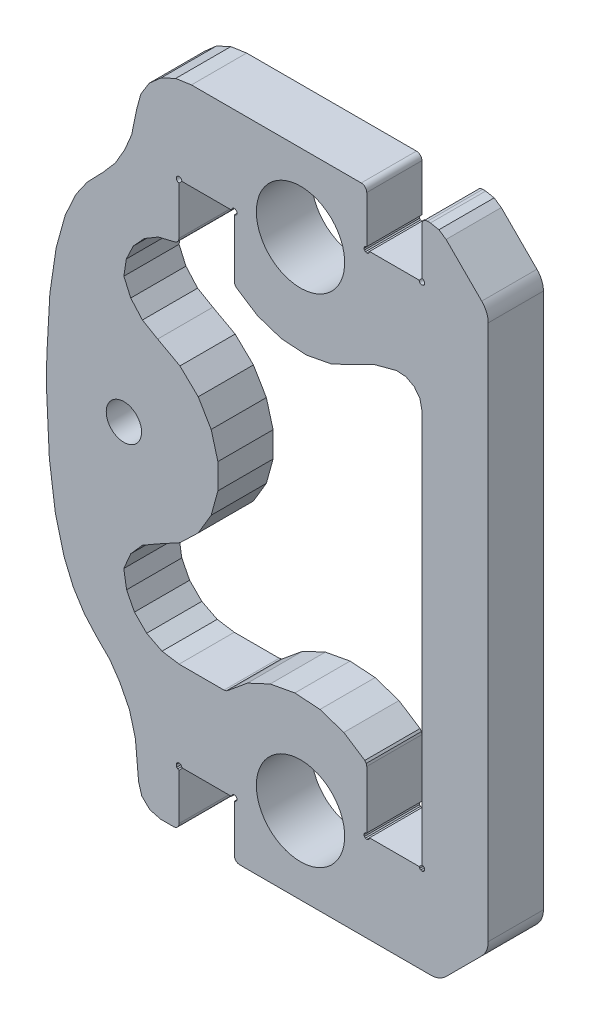
SolidWorks part; units mm, degrees
ref_plane "Plan de face" through (0, 0, 0) normal (0, 0, 1) x (1, 0, 0)
ref_plane "Plan de dessus" through (0, 0, 0) normal (0, 1, 0) x (1, 0, 0)
ref_plane "Plan de droite" through (0, 0, 0) normal (1, 0, 0) x (0, 0, -1)
ref_plane "Plan1" through (0, 0, 0) normal (0, 0, -1) x (-1, 0, 0)
sketch "Esquisse1" plane through (0, 0, 0) normal (0, 0, -1) x (-1, 0, 0)
  line L0 (-17, 50.75) -> (-17, 51.125) construction
  line L1 (-16.75, 51) -> (-17.0786, 51) construction
  line L2 (-12, 50.75) -> (-12, 51.4552) construction
  line L3 (-12.4344, 51) -> (-11.6303, 51) construction
  line L4 (-34, 54.25) -> (-34, 53.1966) construction
  line L5 (-33.75, 54) -> (-34.1708, 54) construction
  line L16 (-8.0397, 5.194) -> (-7.5117, 7.1637)
  line L17 (-7.5117, 7.1637) -> (-6.6375, 8.8943)
  line L18 (-6.6375, 8.8943) -> (-5.7344, 10.2147)
  line L19 (-5.7344, 10.2147) -> (-4.5295, 11.4233)
  line L20 (-4.5295, 11.4233) -> (-3.4265, 12.6596)
  line L21 (-3.4265, 12.6596) -> (-2.4227, 14.24)
  line L22 (-2.4227, 14.24) -> (-1.5781, 16.2347)
  line L23 (-1.5781, 16.2347) -> (-0.788, 19.2781)
  line L24 (-0.788, 19.2781) -> (-0.2469, 23.2647)
  line L25 (-0.2469, 23.2647) -> (-0.0081, 28.2691)
  line L26 (-0.0081, 28.2691) -> (0, 29.5)
  line L27 (0, 29.5) -> (-0.0151, 31.1645)
  line L28 (-0.0151, 31.1645) -> (-0.2937, 36.2357)
  line L29 (-0.2937, 36.2357) -> (-0.8642, 40.1026)
  line L30 (-0.8642, 40.1026) -> (-1.6815, 43.0589)
  line L31 (-1.6815, 43.0589) -> (-2.6679, 45.2058)
  line L32 (-2.6679, 45.2058) -> (-3.6838, 46.6619)
  line L33 (-3.6838, 46.6619) -> (-5.1213, 48.1528)
  line L34 (-5.1213, 48.1528) -> (-6.2218, 49.4228)
  line L35 (-6.2218, 49.4228) -> (-7.0842, 50.913)
  line L36 (-7.0842, 50.913) -> (-7.7057, 52.3865)
  line L37 (-7.7057, 52.3865) -> (-8.155, 54.6026)
  line L38 (-8.155, 54.6026) -> (-8.5346, 55.9968)
  line L39 (-8.5346, 55.9968) -> (-9.297, 57.2242)
  line L40 (-9.297, 57.2242) -> (-10.3785, 58.1823)
  line L41 (-10.3785, 58.1823) -> (-11.6888, 58.7912)
  line L42 (-11.6888, 58.7912) -> (-13.1186, 59)
  line L43 (-13.1186, 59) -> (-28.5, 59)
  line L47 (-29, 58.5) -> (-29, 54.25)
  line L48 (-29, 54.25) -> (-28.875, 54.2165)
  line L49 (-28.875, 54.2165) -> (-28.7835, 54.125)
  line L50 (-28.7835, 54.125) -> (-28.75, 54)
  line L51 (-28.75, 54) -> (-28.7835, 53.875)
  line L52 (-28.7835, 53.875) -> (-28.875, 53.7835)
  line L53 (-28.875, 53.7835) -> (-29, 53.75)
  line L54 (-29, 53.75) -> (-29.125, 53.7835)
  line L55 (-29.125, 53.7835) -> (-29.2165, 53.875)
  line L56 (-29.2165, 53.875) -> (-29.25, 54)
  line L57 (-29.25, 54) -> (-33.75, 54)
  line L67 (-34, 54.25) -> (-34, 58.5)
  line L71 (-34.5, 59) -> (-34.7716, 59)
  line L72 (-34.7716, 59) -> (-35.5369, 58.8478)
  line L73 (-35.5369, 58.8478) -> (-36.1858, 58.4142)
  line L74 (-36.1858, 58.4142) -> (-39.4142, 55.1858)
  line L77 (-40, 53.7716) -> (-40, 5.2284)
  line L80 (-39.4142, 3.8142) -> (-36.1858, 0.5858)
  line L83 (-34.7716, 0) -> (-17.5, 0)
  line L87 (-17, 0.5) -> (-17, 4.75)
  line L88 (-17, 4.75) -> (-17.125, 4.7835)
  line L89 (-17.125, 4.7835) -> (-17.2165, 4.875)
  line L90 (-17.2165, 4.875) -> (-17.25, 5)
  line L91 (-17.25, 5) -> (-17.2165, 5.125)
  line L92 (-17.2165, 5.125) -> (-17.125, 5.2165)
  line L93 (-17.125, 5.2165) -> (-17, 5.25)
  line L94 (-17, 5.25) -> (-16.875, 5.2165)
  line L95 (-16.875, 5.2165) -> (-16.7835, 5.125)
  line L96 (-16.7835, 5.125) -> (-16.75, 5)
  line L97 (-16.75, 5) -> (-12.25, 5)
  line L98 (-12.25, 5) -> (-12.2165, 5.125)
  line L99 (-12.2165, 5.125) -> (-12.125, 5.2165)
  line L100 (-12.125, 5.2165) -> (-12, 5.25)
  line L101 (-12, 5.25) -> (-11.875, 5.2165)
  line L102 (-11.875, 5.2165) -> (-11.7835, 5.125)
  line L103 (-11.7835, 5.125) -> (-11.75, 5)
  line L104 (-11.75, 5) -> (-11.7835, 4.8104)
  line L105 (-11.7835, 4.8104) -> (-11.875, 4.7189)
  line L106 (-11.875, 4.7189) -> (-12, 4.6854)
  line L107 (-12, 4.6854) -> (-12, 0.5)
  line L111 (-11.5, 0) -> (-10.332, 0)
  line L112 (-10.332, 0) -> (-9.3522, 0.2564)
  line L113 (-9.3522, 0.2564) -> (-8.6237, 0.96)
  line L114 (-8.6237, 0.96) -> (-8.3332, 1.9302)
  line L115 (-8.3332, 1.9302) -> (-8.0397, 5.194)
  line L128 (-27.8538, 44.4211) -> (-25.788, 43.4427)
  line L129 (-25.788, 43.4427) -> (-23.5422, 43.0164)
  line L130 (-23.5422, 43.0164) -> (-21.2615, 43.1695)
  line L131 (-21.2615, 43.1695) -> (-19.093, 43.8923)
  line L132 (-19.093, 43.8923) -> (-17.1765, 45.138)
  line L133 (-17.1765, 45.138) -> (-17.0463, 45.3092)
  line L134 (-17.0463, 45.3092) -> (-17, 45.5193)
  line L135 (-17, 45.5193) -> (-17, 50.75)
  line L145 (-16.75, 51) -> (-12.25, 51)
  line L155 (-12, 50.75) -> (-12, 46.4126)
  line L156 (-12, 46.4126) -> (-11.9404, 46.1759)
  line L157 (-11.9404, 46.1759) -> (-11.7758, 45.9956)
  line L158 (-11.7758, 45.9956) -> (-11.5455, 45.9147)
  line L159 (-11.5455, 45.9147) -> (-10.113, 45.5656)
  line L160 (-10.113, 45.5656) -> (-8.8446, 44.814)
  line L161 (-8.8446, 44.814) -> (-7.8506, 43.7251)
  line L162 (-7.8506, 43.7251) -> (-7.2174, 42.3937)
  line L163 (-7.2174, 42.3937) -> (-7, 40.9354)
  line L164 (-7, 40.9354) -> (-7.6191, 39.5311)
  line L165 (-7.6191, 39.5311) -> (-8.678, 38.3351)
  line L166 (-8.678, 38.3351) -> (-10.0601, 37.534)
  line L167 (-10.0601, 37.534) -> (-12.0779, 36.4347)
  line L168 (-12.0779, 36.4347) -> (-13.7325, 34.8404)
  line L169 (-13.7325, 34.8404) -> (-14.906, 32.8648)
  line L170 (-14.906, 32.8648) -> (-15.5144, 30.649)
  line L171 (-15.5144, 30.649) -> (-15.5144, 28.3512)
  line L172 (-15.5144, 28.3512) -> (-14.906, 26.1354)
  line L173 (-14.906, 26.1354) -> (-13.7325, 24.1598)
  line L174 (-13.7325, 24.1598) -> (-12.0779, 22.5655)
  line L175 (-12.0779, 22.5655) -> (-10.0601, 21.4662)
  line L176 (-10.0601, 21.4662) -> (-8.678, 20.6651)
  line L177 (-8.678, 20.6651) -> (-7.6191, 19.4691)
  line L178 (-7.6191, 19.4691) -> (-6.9915, 18.0001)
  line L179 (-6.9915, 18.0001) -> (-7.2447, 16.4549)
  line L180 (-7.2447, 16.4549) -> (-7.9549, 15.0611)
  line L181 (-7.9549, 15.0611) -> (-9.0611, 13.9549)
  line L182 (-9.0611, 13.9549) -> (-10.4549, 13.2447)
  line L183 (-10.4549, 13.2447) -> (-12, 13)
  line L184 (-12, 13) -> (-16.0718, 13)
  line L185 (-16.0718, 13) -> (-16.2705, 13.0412)
  line L186 (-16.2705, 13.0412) -> (-16.4364, 13.1579)
  line L187 (-16.4364, 13.1579) -> (-18.1906, 14.6072)
  line L188 (-18.1906, 14.6072) -> (-20.2521, 15.5702)
  line L189 (-20.2521, 15.5702) -> (-22.4893, 15.9855)
  line L190 (-22.4893, 15.9855) -> (-24.7591, 15.8264)
  line L191 (-24.7591, 15.8264) -> (-26.9165, 15.1032)
  line L192 (-26.9165, 15.1032) -> (-28.8235, 13.862)
  line L193 (-28.8235, 13.862) -> (-28.9537, 13.6908)
  line L194 (-28.9537, 13.6908) -> (-29, 13.4807)
  line L195 (-29, 13.4807) -> (-29, 8.25)
  line L196 (-29, 8.25) -> (-28.875, 8.2165)
  line L197 (-28.875, 8.2165) -> (-28.7835, 8.125)
  line L198 (-28.7835, 8.125) -> (-28.75, 8)
  line L199 (-28.75, 8) -> (-28.7835, 7.875)
  line L200 (-28.7835, 7.875) -> (-28.875, 7.7835)
  line L201 (-28.875, 7.7835) -> (-29, 7.75)
  line L202 (-29, 7.75) -> (-29.125, 7.7835)
  line L203 (-29.125, 7.7835) -> (-29.2165, 7.875)
  line L204 (-29.2165, 7.875) -> (-29.25, 8)
  line L205 (-29.25, 8) -> (-33.75, 8)
  line L206 (-33.75, 8) -> (-33.7835, 7.875)
  line L207 (-33.7835, 7.875) -> (-33.875, 7.7835)
  line L208 (-33.875, 7.7835) -> (-34, 7.75)
  line L209 (-34, 7.75) -> (-34.125, 7.7835)
  line L210 (-34.125, 7.7835) -> (-34.2165, 7.875)
  line L211 (-34.2165, 7.875) -> (-34.25, 8)
  line L212 (-34.25, 8) -> (-34.2165, 8.125)
  line L213 (-34.2165, 8.125) -> (-34.125, 8.2165)
  line L214 (-34.125, 8.2165) -> (-34, 8.25)
  line L215 (-34, 8.25) -> (-34, 43.9022)
  line L216 (-34, 43.9022) -> (-33.8164, 44.7393)
  line L217 (-33.8164, 44.7393) -> (-33.2993, 45.4227)
  line L218 (-33.2993, 45.4227) -> (-32.5437, 45.8269)
  line L219 (-32.5437, 45.8269) -> (-31.6883, 45.8778)
  line L220 (-31.6883, 45.8778) -> (-29.6956, 45.3481)
  line L221 (-29.6956, 45.3481) -> (-27.8538, 44.4211)
  circle A0 centre (-23, 52) radius 4
  circle A1 centre (-23, 7) radius 4
  circle A2 centre (-7, 29.5) radius 1.6
  arc A3 (-40, 53.7716) -> (-39.4142, 55.1858) centre (-38, 53.7716) cw
  arc A4 (-40, 5.2284) -> (-39.4142, 3.8142) centre (-38, 5.2284) ccw
  arc A5 (-36.1858, 0.5858) -> (-34.7716, 0) centre (-34.7716, 2) ccw
  arc A6 (-17.5, 0) -> (-17, 0.5) centre (-17.5, 0.5) ccw
  arc A7 (-12, 0.5) -> (-11.5, 0) centre (-11.5, 0.5) ccw
  arc A8 (-29, 58.5) -> (-28.5, 59) centre (-28.5, 58.5) cw
  arc A9 (-34.5, 59) -> (-34, 58.5) centre (-34.5, 58.5) cw
  arc A10 (-16.75, 51) -> (-17, 50.75) centre (-17, 51) ccw
  arc A11 (-12, 50.75) -> (-12.25, 51) centre (-12, 51) ccw
  arc A12 (-34, 54.25) -> (-33.75, 54) centre (-34, 54) ccw
  dimension "D1" = 3.2
  dimension "D2" = 8
  dimension "D3" = 8
  dimension "D4" = 23
  dimension "D6" = 45
  dimension "D7" = 22.5
  dimension "D8" = 16
  dimension "D9" = 16
  dimension "D10" = 0.25
  dimension "D11" = 0.5
  dimension "D13" = 6
  dimension "D15" = 0.5
  dimension "D5" = 7
  dimension "D12" = 5
  dimension "D14" = 1
extrude "Boss.-Extru.1" add sketch "Esquisse1" against normal blind 5
